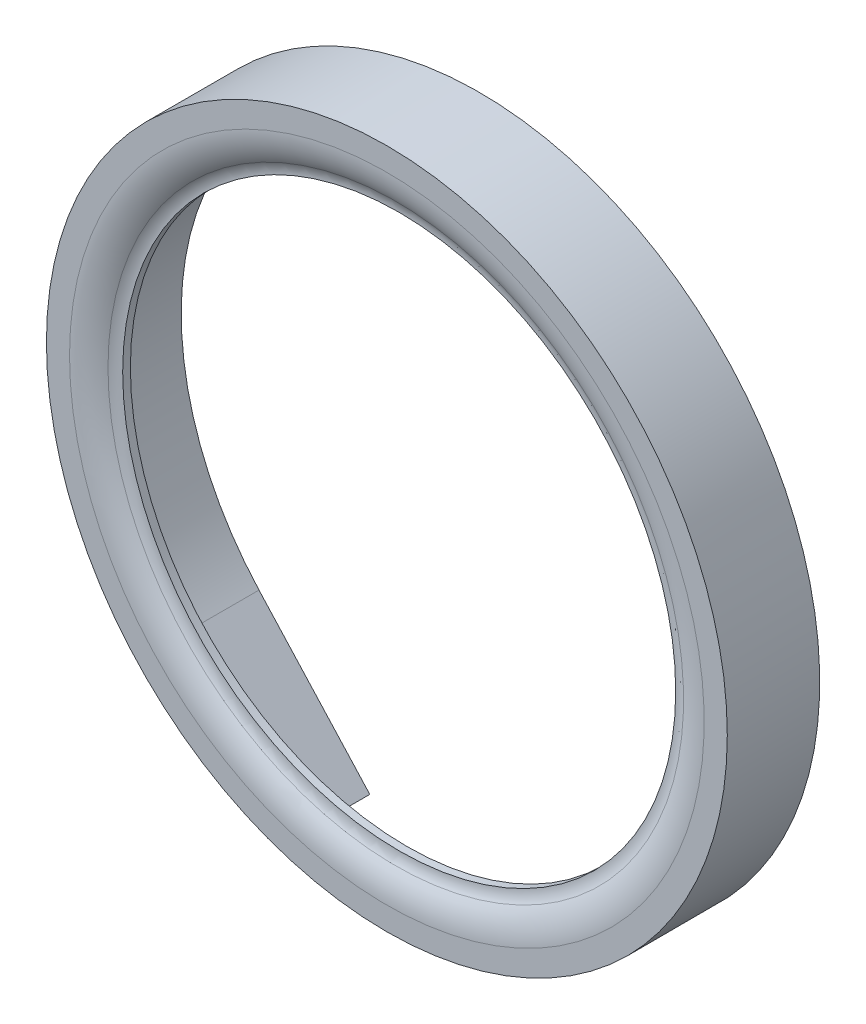
SolidWorks part; units mm, degrees
ref_plane "正面" through (0, 0, 0) normal (0, 0, 1) x (1, 0, 0)
ref_plane "平面" through (0, 0, 0) normal (0, 1, 0) x (1, 0, 0)
ref_plane "右側面" through (0, 0, 0) normal (1, 0, 0) x (0, 0, -1)
sketch "ｽｹｯﾁ1" plane through (0, 0, 0) normal (0, 1, 0) x (1, 0, 0)
  line L0 (17.95, -1.5) -> (17.95, 3.7)
  line L1 (22.1, -2.3) -> (22.1, 3.7)
  line L2 (0, 23.2425) -> (0, -6.1657) construction
  line L3 (-17.85, -1.5) -> (17.85, -1.5) construction
  line L4 (17.95, 3.7) -> (22.1, 3.7)
  line L5 (22.1, -2.3) -> (20.6, -2.3)
  line L6 (18.75, 3.7) -> (-18.75, 3.7) construction
  line L7 (17.85, -1.5) -> (17.85, -1) construction
  arc A0 (17.95, -1.5) -> (18.6825, -1.7211) centre (17.95, -2.8238) cw
  arc A2 (20.6, -2.3) -> (18.6825, -1.7211) centre (20.6, 1.1653) cw
  dimension "D1" = 22.1
  dimension "D2" = 0.8
  dimension "D3" = 1.5
  dimension "D4" = 0.1
revolve "回転1" add sketch "ｽｹｯﾁ1" angle 360 about L2
sketch "ｽｹｯﾁ2" plane through (0, 0, 0) normal (0, 0, 1) x (1, 0, 0)
  line L0 (-8.5, -19.25) -> (-4.7113, -23.4062) construction
  line L1 (-4.7113, -23.4062) -> (4.7113, -23.4062) construction
  line L2 (4.7113, -23.4062) -> (8.5, -19.25) construction
  line L3 (-14.2263, -12.9683) -> (-8.5, -19.25)
  line L4 (-8.5, -19.25) -> (8.5, -19.25)
  line L5 (8.5, -19.25) -> (14.2263, -12.9683)
  line L6 (-14.2263, -12.9683) -> (-8.5, -19.25) construction
  line L7 (-8.5, -19.25) -> (8.5, -19.25) construction
  line L8 (8.5, -19.25) -> (14.2263, -12.9683) construction
  line L9 (-14.3002, -13.0356) -> (-8.5739, -19.3174)
  line L10 (-8.5739, -19.3174) -> (-4.7555, -23.5062)
  line L11 (-4.7555, -23.5062) -> (4.7555, -23.5062)
  line L12 (4.7555, -23.5062) -> (8.5739, -19.3174)
  line L13 (8.5739, -19.3174) -> (14.3002, -13.0356)
  arc A0 (14.3002, -13.0356) -> (-14.3002, -13.0356) centre (0, 0) ccw
  arc A3 (14.2263, -12.9683) -> (-14.2263, -12.9683) centre (0, 0) ccw
  arc A4 (14.2263, -12.9683) -> (-14.2263, -12.9683) centre (0, 0) ccw construction
  dimension "D1" = 0
  dimension "D2" = 0.1
extrude "ｶｯﾄ - 押し出し2" cut sketch "ｽｹｯﾁ2" along normal blind 1 and the other way through all
sketch "ｽｹｯﾁ3" plane through (0, 0, -3.7) normal (0, 0, -1) x (-1, 0, 0)
  circle A0 centre (0, 20.35) radius 0.9
  circle A1 centre (0, 20.35) radius 1.75 construction
  circle A2 centre (0, 0) radius 22.1 construction
  dimension "D1" = 1.8
  dimension "D2" = 3.5
extrude "ｶｯﾄ - 押し出し3" cut sketch "ｽｹｯﾁ3" against normal blind 4
pattern_circular "円形ﾊﾟﾀｰﾝ1" count 3 over 360 about axis through (0, 0, 0) along (0, 0, 1) of "ｶｯﾄ - 押し出し3"
sketch "ｽｹｯﾁ4" plane through (0, 0, 0) normal (0, 0, 1) x (1, 0, 0)
  line L3 (-12.64, -13.8489) -> (-5.0898, -20.74)
  line L4 (-5.0898, -20.74) -> (5.0898, -20.74)
  line L5 (5.0898, -20.74) -> (12.64, -13.8489)
  line L6 (-12.64, -13.8489) -> (-5.0898, -20.74)
  line L7 (-5.0898, -20.74) -> (5.0898, -20.74)
  line L8 (5.0898, -20.74) -> (12.64, -13.8489)
  arc A1 (12.64, -13.8489) -> (-12.64, -13.8489) centre (0, 0) ccw
  arc A2 (12.64, -13.8489) -> (-12.64, -13.8489) centre (0, 0) ccw
  dimension "D1" = 0
extrude "ｶｯﾄ - 押し出し4" [suppressed] cut sketch "ｽｹｯﾁ4" against normal through all
equation "\"D1@ｽｹｯﾁ1\"=21.50mm+0.6mm"
